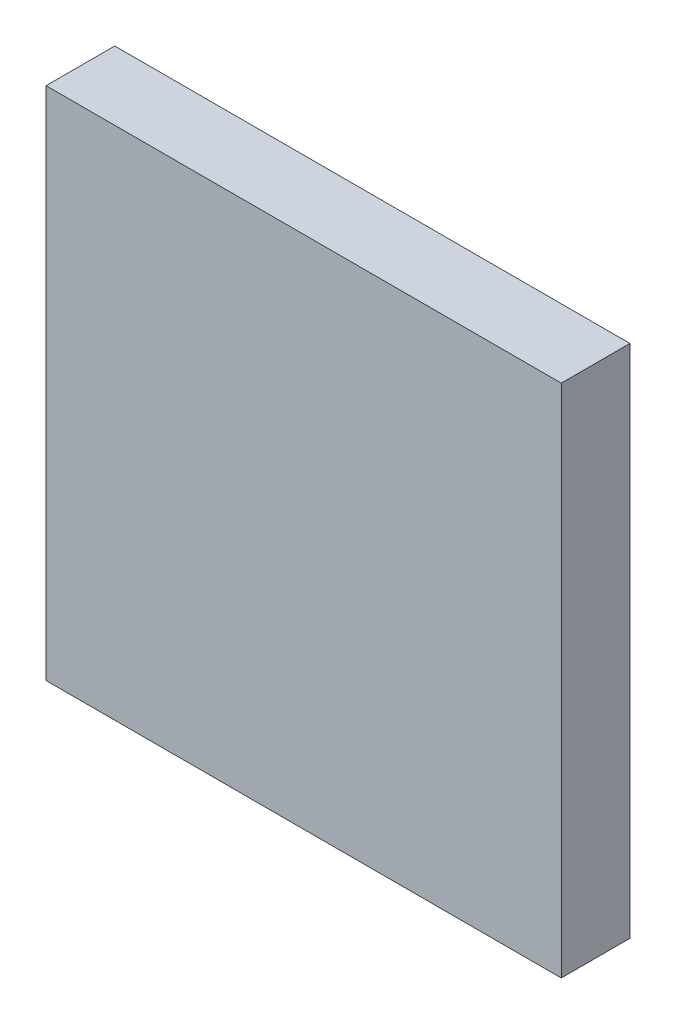
SolidWorks part; units mm, degrees
ref_plane "前视基准面" through (0, 0, 0) normal (0, 0, 1) x (1, 0, 0)
ref_plane "上视基准面" through (0, 0, 0) normal (0, 1, 0) x (1, 0, 0)
ref_plane "右视基准面" through (0, 0, 0) normal (1, 0, 0) x (0, 0, -1)
sketch "草图1" plane through (0, 0, 0) normal (0, 0, 1) x (1, 0, 0)
  line L1 (-80.6435, 21.5462) -> (-50.6435, 21.5462)
  line L2 (-80.6435, 21.5462) -> (-80.6435, 51.5462)
  line L3 (-80.6435, 51.5462) -> (-50.6435, 51.5462)
  line L4 (-50.6435, 21.5462) -> (-50.6435, 51.5462)
  line L5 (-80.6435, 21.5462) -> (-50.6435, 51.5462) construction
  line L6 (-80.6435, 51.5462) -> (-50.6435, 21.5462) construction
  point P0 (-65.6435, 36.5462)
extrude "凸台-拉伸1" add sketch "草图1" along normal blind 4
sketch "草图2" plane through (0, 0, 0) normal (0, 0, -1) x (-1, 0, 0)
  line L0 (50.6435, 36.5462) -> (80.6435, 36.5462)
  line L1 (50.6435, 21.5462) -> (50.6435, 51.5462) construction
  line L2 (80.6435, 51.5462) -> (80.6435, 21.5462) construction
  line L4 (55.6435, 35.5462) -> (75.6435, 35.5462)
  line L5 (55.6435, 35.5462) -> (55.6435, 37.5462)
  line L6 (55.6435, 37.5462) -> (75.6435, 37.5462)
  line L7 (75.6435, 35.5462) -> (75.6435, 37.5462)
  line L8 (55.6435, 35.5462) -> (75.6435, 37.5462) construction
  line L9 (55.6435, 37.5462) -> (75.6435, 35.5462) construction
  point P6 (65.6435, 36.5462)
extrude "凸台-拉伸2" add sketch "草图2" along normal blind 2 contours L4 L7 L0 L5 | L0 L7 L6 L5
